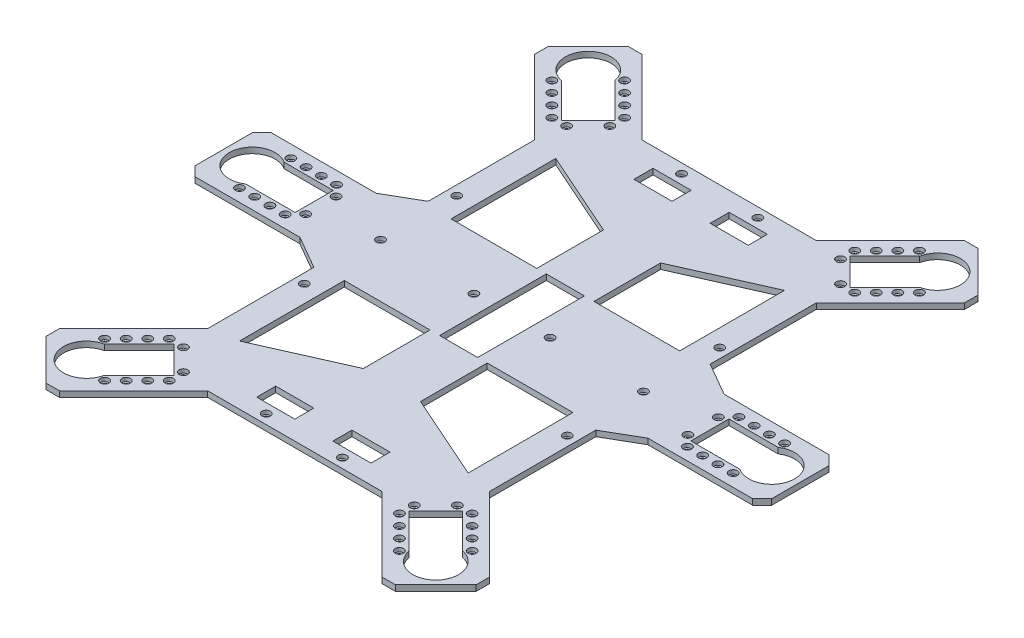
SolidWorks part; units mm, degrees
ref_plane "Front" through (0, 0, 0) normal (0, 0, 1) x (1, 0, 0)
ref_plane "Top" through (0, 0, 0) normal (0, 1, 0) x (1, 0, 0)
ref_plane "Right" through (0, 0, 0) normal (1, 0, 0) x (0, 0, -1)
sketch "草图1" plane through (0, 0, 0) normal (0, 1, 0) x (1, 0, 0)
  line L0 (-45.7157, 114) -> (45.7157, 114)
  line L1 (-74, 0) -> (74, 0) construction
  line L2 (74, -30) -> (91.3205, -20)
  line L3 (91.3205, -20) -> (146.3205, -20)
  line L4 (151.3205, -15) -> (151.3205, 15)
  line L5 (-60, 100) -> (60, -100) construction
  line L6 (-60, -100) -> (60, 100) construction
  line L7 (74, -30) -> (74, -85.7157)
  line L8 (-45.7157, -114) -> (45.7157, -114)
  line L9 (-74, 85.7157) -> (-74, 30)
  line L10 (146.3205, 20) -> (91.3205, 20)
  line L11 (74, 30) -> (91.3205, 20)
  line L12 (0, 100) -> (0, -100) construction
  line L13 (-74, 30) -> (-91.3205, 20)
  line L14 (-146.3205, 20) -> (-91.3205, 20)
  line L15 (-151.3205, -15) -> (-151.3205, 15)
  line L16 (-91.3205, -20) -> (-146.3205, -20)
  line L17 (-74, -30) -> (-91.3205, -20)
  line L18 (-74, -30) -> (-74, -85.7157)
  line L19 (74, 85.7157) -> (74, 30)
  line L20 (91.6777, 152.8909) -> (112.8909, 131.6777)
  line L21 (74, 85.7157) -> (112.8909, 124.6066)
  line L22 (45.7157, 114) -> (84.6066, 152.8909)
  line L23 (-74, 85.7157) -> (-112.8909, 124.6066)
  line L24 (-91.6777, 152.8909) -> (-112.8909, 131.6777)
  line L25 (-45.7157, 114) -> (-84.6066, 152.8909)
  line L26 (74, -85.7157) -> (112.8909, -124.6066)
  line L27 (91.6777, -152.8909) -> (112.8909, -131.6777)
  line L28 (45.7157, -114) -> (84.6066, -152.8909)
  line L29 (-74, -85.7157) -> (-112.8909, -124.6066)
  line L30 (-91.6777, -152.8909) -> (-112.8909, -131.6777)
  line L31 (-45.7157, -114) -> (-84.6066, -152.8909)
  line L32 (-84.6066, 152.8909) -> (-91.6777, 152.8909)
  line L33 (-112.8909, 131.6777) -> (-112.8909, 124.6066)
  line L34 (-151.3205, 15) -> (-146.3205, 20)
  line L35 (-146.3205, -20) -> (-151.3205, -15)
  line L36 (-112.8909, -124.6066) -> (-112.8909, -131.6777)
  line L37 (-84.6066, -152.8909) -> (-91.6777, -152.8909)
  line L38 (84.6066, -152.8909) -> (91.6777, -152.8909)
  line L39 (112.8909, -131.6777) -> (112.8909, -124.6066)
  line L40 (146.3205, -20) -> (151.3205, -15)
  line L41 (151.3205, 15) -> (146.3205, 20)
  line L42 (112.8909, 124.6066) -> (112.8909, 131.6777)
  line L43 (84.6066, 152.8909) -> (91.6777, 152.8909)
  point P0 (0, 0)
  point P12 (74, 30)
  point P16 (74, -30)
extrude "凸台-拉伸1" add sketch "草图1" along normal blind 3
sketch "草图2" plane through (0, 3, 0) normal (0, 1, 0) x (1, 0, 0)
  line L0 (151.3205, 0) -> (87.3942, 0) construction
  line L1 (151.3205, -15) -> (151.3205, 15) construction
  line L2 (103.8205, -10) -> (103.8205, 10)
  line L3 (103.8205, 10) -> (129.6873, 10)
  line L4 (103.8205, -10) -> (129.6873, -10)
  arc A0 (129.6873, -10) -> (129.6873, 10) centre (136.3205, 0) ccw
  point P11 (103.8205, 0)
  dimension "D2" = 24
  dimension "D1" = 15
  dimension "D3" = 20
  dimension "D4" = 32.5
extrude "切除-拉伸1" cut sketch "草图2" against normal up to next
sketch "草图3" plane through (0, 3, 0) normal (0, 1, 0) x (1, 0, 0)
  line L0 (129.6873, 10) -> (103.8205, 10) construction
  line L1 (103.8205, 10) -> (103.8205, -10) construction
  line L2 (151.3205, 0) -> (86.0016, 0) construction
  line L3 (151.3205, -15) -> (151.3205, 15) construction
  point P0 (105.5705, 13.5)
  point P10 (100.3205, 8)
  point P12 (113.5705, 13.5)
  point P13 (121.5705, 13.5)
  point P14 (129.5705, 13.5)
  point P15 (129.5705, -13.5)
  point P16 (121.5705, -13.5)
  point P17 (113.5705, -13.5)
  point P18 (105.5705, -13.5)
  point P19 (100.3205, -8)
  dimension "D1" = 3.5
  dimension "D2" = 1.75
  dimension "D4" = 3.5
  dimension "D5" = 2
  dimension "D3" = 4
hole_wizard "M2 凹头盖螺钉的柱形沉头孔2" positions "3D草图1" profile "草图9" counterbore size "M2" standard "ANSI Metric" end condition through all
sketch3d "3D草图1"
  point P0 (100.3205, 3, -8)
  point P3 (105.5705, 3, -13.5)
  point P6 (113.5705, 3, -13.5)
  point P9 (121.5705, 3, -13.5)
  point P12 (129.5705, 3, -13.5)
  point P15 (100.3205, 3, 8)
  point P18 (105.5705, 3, 13.5)
  point P21 (113.5705, 3, 13.5)
  point P24 (121.5705, 3, 13.5)
  point P27 (129.5705, 3, 13.5)
sketch "草图9" plane through (100.3205, 3, -8) normal (1, 0, 0) x (0, 0, 1)
  line L0 (0, 0) -> (0, 3)
  line L1 (0, 3) -> (1.2, 3)
  line L3 (1.2, 3) -> (1.2, 2)
  line L4 (1.2, 2) -> (2.2, 2)
  line L5 (2.2, 2) -> (2.2, 0)
  line L7 (2.2, 0) -> (0, 0)
  line L11 (0, -6.35) -> (0, 107.95) construction
  dimension "通孔孔直径" = 2.4
  dimension "通孔孔深度" = 3
  dimension "柱形沉头孔直径" = 4.4
  dimension "柱形沉头孔深度" = 2
sketch "草图10" plane through (0, 3, 0) normal (0, 1, 0) x (1, 0, 0)
  line L0 (102.2843, 142.2843) -> (57.3662, 97.3662) construction
  line L1 (112.8909, 131.6777) -> (91.6777, 152.8909) construction
  line L2 (75.7678, 101.6256) -> (61.6256, 115.7678)
  line L3 (61.6256, 115.7678) -> (79.9162, 134.0583)
  line L4 (75.7678, 101.6256) -> (94.0583, 119.9162)
  arc A0 (94.0583, 119.9162) -> (79.9162, 134.0583) centre (91.6777, 131.6777) ccw
  point P9 (68.6967, 108.6967)
  dimension "D1" = 15
  dimension "D2" = 32.5
extrude "切除-拉伸2" cut sketch "草图10" against normal up to next
sketch "草图16" plane through (0, 3, 0) normal (0, 1, 0) x (1, 0, 0)
  line L0 (102.2843, 142.2843) -> (58.019, 98.019) construction
  line L1 (112.8909, 131.6777) -> (91.6777, 152.8909) construction
  line L2 (61.6256, 115.7678) -> (75.7678, 101.6256) construction
  line L3 (79.9162, 134.0583) -> (61.6256, 115.7678) construction
  line L4 (60.3882, 119.4801) -> (80.2149, 139.3067) construction
  point P0 (60.3882, 119.4801)
  point P1 (60.565, 111.8787)
  point P12 (66.045, 125.1369)
  point P13 (71.7019, 130.7938)
  point P14 (77.3588, 136.4506)
  point P15 (96.4506, 117.3588)
  point P16 (90.7938, 111.7019)
  point P17 (85.1369, 106.045)
  point P18 (79.4801, 100.3882)
  point P19 (71.8787, 100.565)
  dimension "D1" = 3.5
  dimension "D2" = 2
  dimension "D3" = 1.75
  dimension "D4" = 3.5
  dimension "D5" = 8
  dimension "D6" = 8
  dimension "D7" = 8
hole_wizard "M2 凹头盖螺钉的柱形沉头孔3" positions "3D草图3" profile "草图17" counterbore size "M2" standard "ANSI Metric" end condition through all
sketch3d "3D草图3"
  point P0 (60.3882, 3, -119.4801)
  point P3 (66.045, 3, -125.1369)
  point P6 (71.7019, 3, -130.7938)
  point P9 (77.3588, 3, -136.4506)
  point P12 (60.565, 3, -111.8787)
  point P15 (71.8787, 3, -100.565)
  point P18 (79.4801, 3, -100.3882)
  point P21 (85.1369, 3, -106.045)
  point P24 (90.7938, 3, -111.7019)
  point P27 (96.4506, 3, -117.3588)
sketch "草图17" plane through (60.3882, 3, -119.4801) normal (1, 0, 0) x (0, 0, 1)
  line L0 (0, 0) -> (0, 3)
  line L1 (0, 3) -> (1.2, 3)
  line L3 (1.2, 3) -> (1.2, 2)
  line L4 (1.2, 2) -> (2.2, 2)
  line L5 (2.2, 2) -> (2.2, 0)
  line L7 (2.2, 0) -> (0, 0)
  line L11 (0, -6.35) -> (0, 107.95) construction
  dimension "通孔孔直径" = 2.4
  dimension "通孔孔深度" = 3
  dimension "柱形沉头孔直径" = 4.4
  dimension "柱形沉头孔深度" = 2
mirror "镜向5" about plane through (0, 0, 0) normal (1, 0, 0) of "切除-拉伸1", "M2 凹头盖螺钉的柱形沉头孔2"
mirror "镜向6" about plane through (0, 0, 0) normal (1, 0, 0) of "切除-拉伸2", "M2 凹头盖螺钉的柱形沉头孔3"
mirror "镜向7" about plane through (0, 0, 0) normal (0, 0, 1) of "切除-拉伸2", "M2 凹头盖螺钉的柱形沉头孔3", "镜向6"
sketch "草图18" plane through (0, 3, 0) normal (0, 1, 0) x (1, 0, 0)
  line L0 (0, 114) -> (0, -114) construction
  line L1 (45.7157, 114) -> (-45.7157, 114) construction
  line L2 (-45.7157, -114) -> (45.7157, -114) construction
  line L3 (-151.3205, 0) -> (151.3205, 0) construction
  line L4 (-151.3205, 15) -> (-151.3205, -15) construction
  line L5 (-60, -28) -> (-15, -28)
  line L6 (-15, -28) -> (-15, -63)
  line L7 (-15, -63) -> (-60, -83)
  line L8 (-60, -83) -> (-60, -28)
  line L12 (10, -94) -> (30, -94)
  line L13 (-10, -94) -> (-30, -94)
  line L14 (-10, -94) -> (-10, -104)
  line L15 (-10, -104) -> (-30, -104)
  line L16 (-30, -94) -> (-30, -104)
  line L17 (-10, -94) -> (-30, -104) construction
  line L18 (-10, -104) -> (-30, -94) construction
  line L19 (10, -104) -> (30, -104)
  line L20 (10, -94) -> (10, -104)
  line L21 (30, -94) -> (30, -104)
  line L22 (15, -63) -> (60, -83)
  line L23 (60, -83) -> (60, -28)
  line L25 (15, -28) -> (15, -63)
  line L26 (60, -28) -> (15, -28)
  line L27 (-10, 104) -> (-30, 104)
  line L28 (-30, 94) -> (-30, 104)
  line L29 (-10, 94) -> (-30, 94)
  line L30 (-10, 94) -> (-10, 104)
  line L31 (30, 94) -> (30, 104)
  line L32 (10, 104) -> (30, 104)
  line L33 (10, 94) -> (10, 104)
  line L34 (10, 94) -> (30, 94)
  line L35 (15, 63) -> (60, 83)
  line L36 (60, 83) -> (60, 28)
  line L37 (60, 28) -> (15, 28)
  line L38 (15, 28) -> (15, 63)
  line L39 (-15, 28) -> (-15, 63)
  line L40 (-60, 28) -> (-15, 28)
  line L41 (-60, 83) -> (-60, 28)
  line L42 (-15, 63) -> (-60, 83)
  point P17 (-20, -99)
  point P32 (0, -20)
  point P33 (0, -10)
  dimension "D5" = 60
  dimension "D6" = 45
  dimension "D7" = 55
  dimension "D8" = 35
  dimension "D9" = 20
  dimension "D10" = 10
  dimension "D11" = 10
  dimension "D12" = 10
extrude "切除-拉伸3" cut sketch "草图18" against normal up to next
sketch "草图19" plane through (0, 3, 0) normal (0, 1, 0) x (1, 0, 0)
  line L0 (0, 114) -> (0, -114) construction
  line L1 (45.7157, 114) -> (-45.7157, 114) construction
  line L2 (-45.7157, -114) -> (45.7157, -114) construction
  line L3 (-151.3205, 0) -> (151.3205, 0) construction
  line L4 (-151.3205, 15) -> (-151.3205, -15) construction
  line L5 (-10, 94) -> (-10, 104) construction
  point P0 (-20, 109)
  point P14 (20, 109)
  point P15 (20, -109)
  point P16 (-20, -109)
  point P17 (-20, 0)
  point P18 (20, 0)
  dimension "D1" = 5
  dimension "D2" = 10
hole_wizard "M2 凹头盖螺钉的柱形沉头孔4" positions "3D草图4" profile "草图20" counterbore size "M2" standard "ANSI Metric" end condition through all
sketch3d "3D草图4"
  point P0 (-20, 3, 109)
  point P3 (20, 3, 109)
  point P6 (-20, 3, -109)
  point P9 (20, 3, -109)
sketch "草图20" plane through (-20, 3, 109) normal (1, 0, 0) x (0, 0, 1)
  line L0 (0, 0) -> (0, 3)
  line L1 (0, 3) -> (1.2, 3)
  line L3 (1.2, 3) -> (1.2, 2)
  line L4 (1.2, 2) -> (2.2, 2)
  line L5 (2.2, 2) -> (2.2, 0)
  line L7 (2.2, 0) -> (0, 0)
  line L11 (0, -6.35) -> (0, 107.95) construction
  dimension "通孔孔直径" = 2.4
  dimension "通孔孔深度" = 3
  dimension "柱形沉头孔直径" = 4.4
  dimension "柱形沉头孔深度" = 2
sketch "草图21" plane through (0, 3, 0) normal (0, 1, 0) x (1, 0, 0)
  line L0 (-74, 85.7157) -> (-74, 30) construction
  line L1 (74, 30) -> (74, 85.7157) construction
  line L2 (-60, 28) -> (-15, 28) construction
  line L3 (15, 28) -> (60, 28) construction
  point P0 (-69, 40)
  point P1 (69, 40)
  point P6 (-69, 0)
  point P11 (69, 0)
  dimension "D1" = 5
  dimension "D2" = 5
  dimension "D3" = 12
  dimension "D4" = 12
  dimension "D5" = 40
hole_wizard "M2 凹头盖螺钉的柱形沉头孔5" positions "3D草图5" profile "草图22" counterbore size "M2" standard "ANSI Metric" end condition through all
sketch3d "3D草图5"
  point P0 (-69, 3, -40)
  point P3 (69, 3, -40)
sketch "草图22" plane through (-69, 3, -40) normal (1, 0, 0) x (0, 0, 1)
  line L0 (0, 0) -> (0, 3)
  line L1 (0, 3) -> (1.2, 3)
  line L3 (1.2, 3) -> (1.2, 2)
  line L4 (1.2, 2) -> (2.2, 2)
  line L5 (2.2, 2) -> (2.2, 0)
  line L7 (2.2, 0) -> (0, 0)
  line L11 (0, -6.35) -> (0, 107.95) construction
  dimension "通孔孔直径" = 2.4
  dimension "通孔孔深度" = 3
  dimension "柱形沉头孔直径" = 4.4
  dimension "柱形沉头孔深度" = 2
mirror "镜向8" about plane through (0, 0, 0) normal (0, 0, 1) of "M2 凹头盖螺钉的柱形沉头孔5"
hole_wizard "M2 凹头盖螺钉的柱形沉头孔6" positions "3D草图6" profile "草图23" counterbore size "M2" standard "ANSI Metric" end condition through all
sketch3d "3D草图6"
  point P0 (-69, 3, 0)
  point P3 (69, 3, 0)
sketch "草图23" plane through (-69, 3, 0) normal (1, 0, 0) x (0, 0, 1)
  line L0 (0, 0) -> (0, 3)
  line L1 (0, 3) -> (1.2, 3)
  line L3 (1.2, 3) -> (1.2, 2)
  line L4 (1.2, 2) -> (2.2, 2)
  line L5 (2.2, 2) -> (2.2, 0)
  line L7 (2.2, 0) -> (0, 0)
  line L11 (0, -6.35) -> (0, 107.95) construction
  dimension "通孔孔直径" = 2.4
  dimension "通孔孔深度" = 3
  dimension "柱形沉头孔直径" = 4.4
  dimension "柱形沉头孔深度" = 2
sketch "草图24" plane through (0, 3, 0) normal (0, 1, 0) x (1, 0, 0)
  line L3 (-10, 28) -> (10, 28)
  line L4 (-10, 28) -> (-10, -28)
  line L5 (-10, -28) -> (10, -28)
  line L6 (10, 28) -> (10, -28)
  line L7 (-10, 28) -> (10, -28) construction
  line L8 (-10, -28) -> (10, 28) construction
  point P0 (0, 0)
  dimension "D1" = 20
  dimension "D2" = 56
extrude "切除-拉伸4" cut sketch "草图24" against normal blind 10
hole_wizard "M2 凹头盖螺钉的柱形沉头孔7" positions "3D草图7" profile "草图25" counterbore size "M2" standard "ANSI Metric" end condition through all
sketch3d "3D草图7"
  point P0 (-20, 3, 0)
  point P3 (20, 3, 0)
sketch "草图25" plane through (-20, 3, 0) normal (1, 0, 0) x (0, 0, 1)
  line L0 (0, 0) -> (0, 3)
  line L1 (0, 3) -> (1.2, 3)
  line L3 (1.2, 3) -> (1.2, 2)
  line L4 (1.2, 2) -> (2.2, 2)
  line L5 (2.2, 2) -> (2.2, 0)
  line L7 (2.2, 0) -> (0, 0)
  line L11 (0, -6.35) -> (0, 107.95) construction
  dimension "通孔孔直径" = 2.4
  dimension "通孔孔深度" = 3
  dimension "柱形沉头孔直径" = 4.4
  dimension "柱形沉头孔深度" = 2
